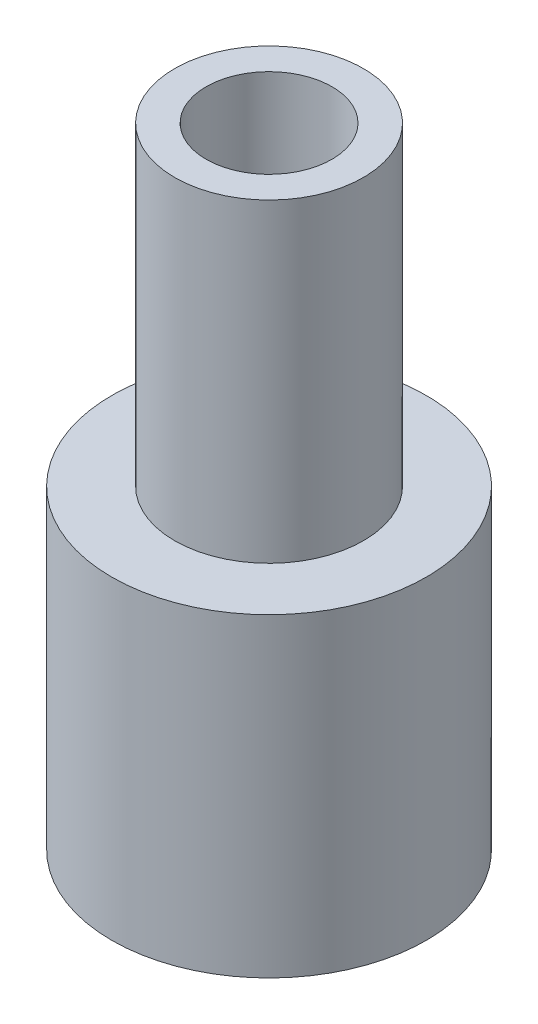
SolidWorks part; units mm, degrees
material "黄铜"
ref_plane "前视基准面" through (0, 0, 0) normal (0, 0, 1) x (1, 0, 0)
ref_plane "上视基准面" through (0, 0, 0) normal (0, 1, 0) x (1, 0, 0)
ref_plane "右视基准面" through (0, 0, 0) normal (1, 0, 0) x (0, 0, -1)
sketch "草图1" plane through (0, 0, 0) normal (0, 1, 0) x (1, 0, 0)
  circle A0 centre (0, 0) radius 5
extrude "凸台-拉伸1" add sketch "草图1" along normal blind 10
sketch "草图2" plane through (0, 10, 0) normal (0, 1, 0) x (1, 0, 0)
  circle A0 centre (0, 0) radius 3
extrude "凸台-拉伸2" add sketch "草图2" along normal blind 10
sketch "草图3" plane through (0, 20, 0) normal (0, 1, 0) x (1, 0, 0)
  circle A0 centre (0, 0) radius 2
  point P3 (0, 0)
extrude "切除-拉伸1" cut sketch "草图3" against normal up to surface (10 mm away) up to face at (0, 10, 3)
